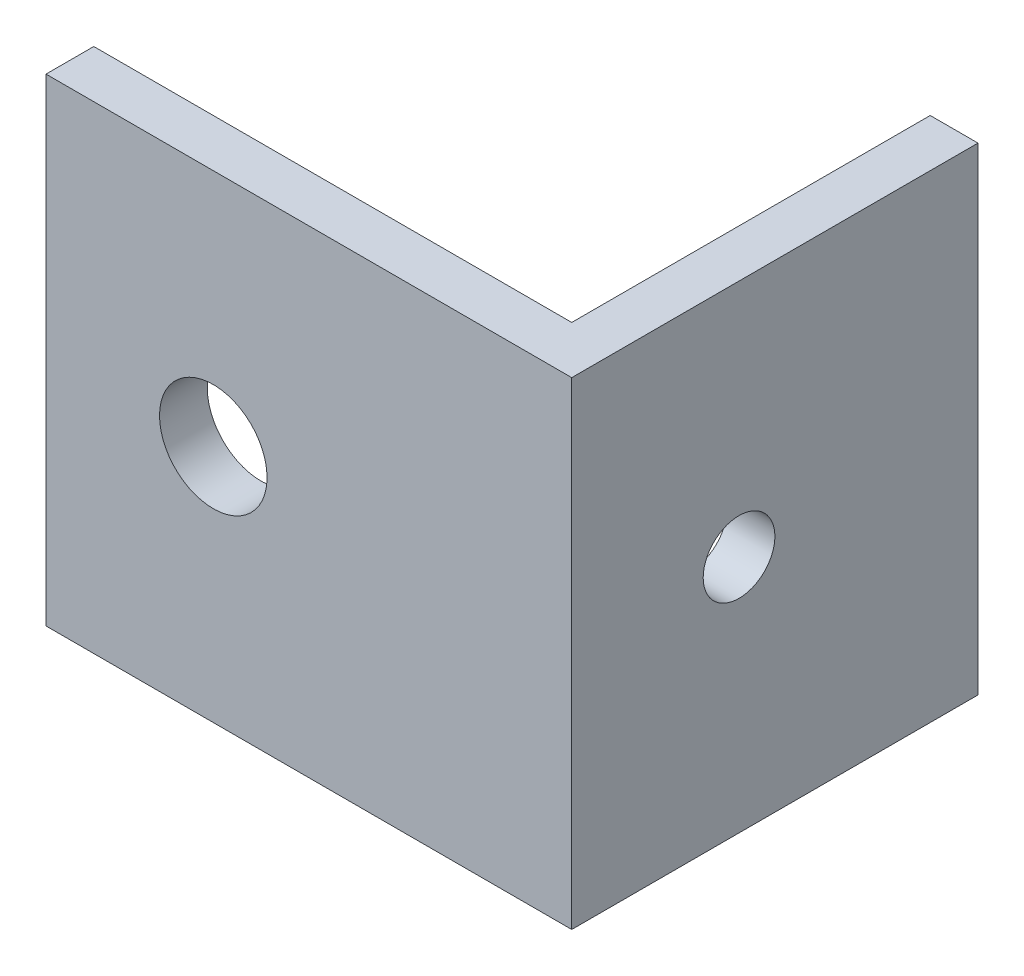
SolidWorks part; units mm, degrees
ref_plane "前视基准面" through (0, 0, 0) normal (0, 0, 1) x (1, 0, 0)
ref_plane "上视基准面" through (0, 0, 0) normal (0, 1, 0) x (1, 0, 0)
ref_plane "右视基准面" through (0, 0, 0) normal (1, 0, 0) x (0, 0, -1)
sketch "Sketch2" plane through (0, 0, 0) normal (0, 1, 0) x (1, 0, 0)
  line L1 (-20, 0) -> (0, 0)
  line L2 (-20, 0) -> (-20, -2)
  line L3 (-20, -2) -> (2, -2)
  line L6 (0, 0) -> (0, 15)
  line L7 (0, 15) -> (2, 15)
  line L8 (2, -2) -> (2, 15)
  point P7 (2, -2.0717)
  point P8 (2, -1.897)
  dimension "D1" = 2
  dimension "D2" = 2
  dimension "D3" = 20
  dimension "D4" = 15
extrude "Boss-Extrude1" add sketch "Sketch2" along normal blind 20
sketch "Sketch3" plane through (0, 0, 0) normal (0, 0, -1) x (-1, 0, 0)
  line L0 (20, 20) -> (20, 0) construction
  line L1 (20, 10) -> (-2, 10) construction
  line L2 (-2, 20) -> (-2, 0) construction
  circle A0 centre (13, 10) radius 2.25
  point P4 (13, 10)
  dimension "D1" = 4.5
  dimension "D2" = 7
extrude "Cut-Extrude1" cut sketch "Sketch3" against normal through all
sketch "Sketch4" plane through (0, 0, 0) normal (-1, 0, 0) x (0, 0, 1)
  line L0 (0, 20) -> (0, 0) construction
  line L1 (-15, 10) -> (0, 10) construction
  line L2 (-15, 20) -> (-15, 0) construction
  line L3 (0, 20) -> (0, 0) construction
  circle A0 centre (-5, 10) radius 1.5
  point P10 (-5, 10)
  dimension "D1" = 3
  dimension "D2" = 5
extrude "Cut-Extrude2" cut sketch "Sketch4" against normal through all
